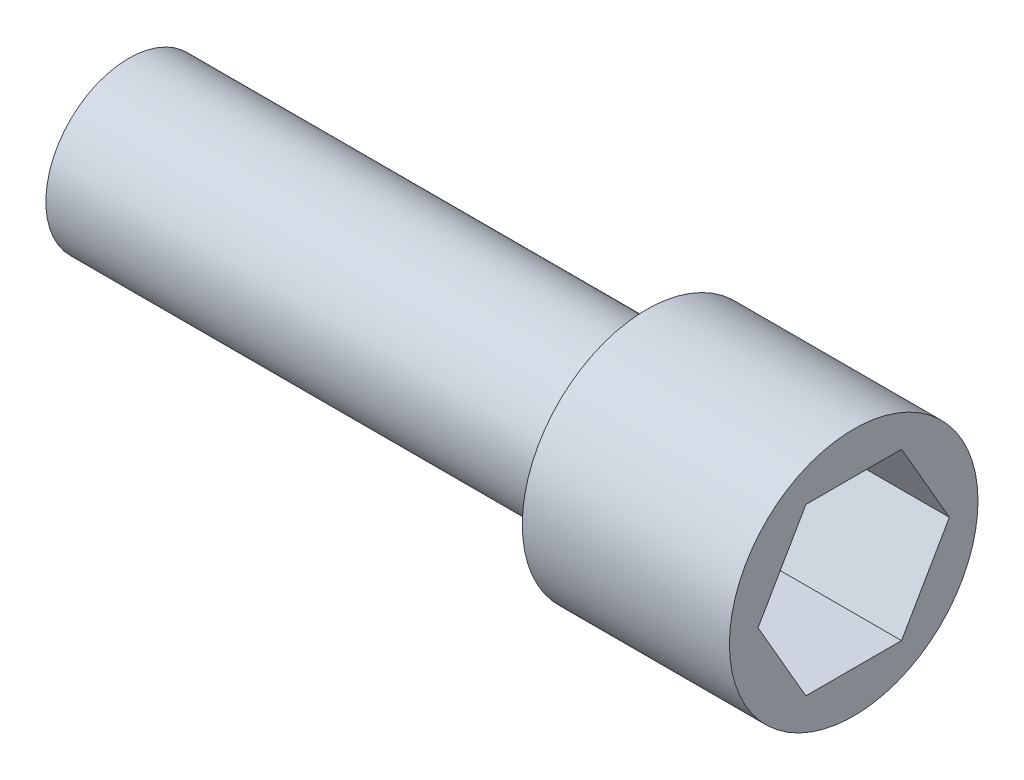
SolidWorks part; units mm, degrees
material "AISI 1010 Steel, hot rolled bar"
ref_plane "Front Plane" through (0, 0, 0) normal (0, 0, 1) x (1, 0, 0)
ref_plane "Top Plane" through (0, 0, 0) normal (0, 1, 0) x (1, 0, 0)
ref_plane "Right Plane" through (0, 0, 0) normal (1, 0, 0) x (0, 0, -1)
sketch "Sketch1" plane through (0, 0, 0) normal (0, 0, 1) x (1, 0, 0)
  line L0 (0, 0) -> (0, 4)
  line L1 (0, 4) -> (25, 4)
  line L2 (25, 4) -> (25, 6)
  line L3 (25, 6) -> (35, 6)
  line L4 (35, 6) -> (35, 0)
  line L5 (35, 0) -> (0, 0)
  dimension "D1" = 35
  dimension "D2" = 4
  dimension "D3" = 6
  dimension "D4" = 10
revolve "Revolve1" add sketch "Sketch1" angle 360 about L5
sketch "Sketch2" plane through (35, 0, 0) normal (1, 0, 0) x (0, 0, -1)
  line L1 (4.6188, 0) -> (2.3094, 4)
  line L2 (2.3094, 4) -> (-2.3094, 4)
  line L3 (-2.3094, 4) -> (-4.6188, 0)
  line L4 (-4.6188, 0) -> (-2.3094, -4)
  line L5 (-2.3094, -4) -> (2.3094, -4)
  line L6 (2.3094, -4) -> (4.6188, 0)
  circle A0 centre (0, 0) radius 4 construction
  dimension "D1" = 8
extrude "Cut-Extrude1" cut sketch "Sketch2" against normal blind 7
